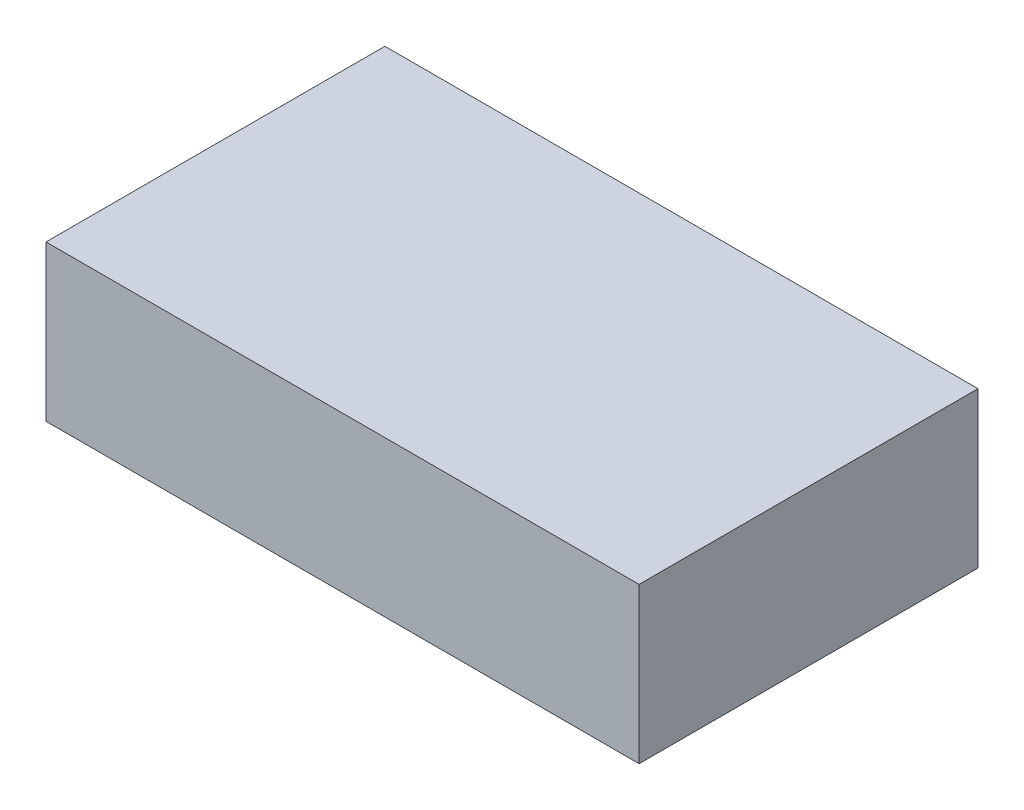
SolidWorks part; units mm, degrees
ref_plane "Front Plane" through (0, 0, 0) normal (0, 0, 1) x (1, 0, 0)
ref_plane "Top Plane" through (0, 0, 0) normal (0, 1, 0) x (1, 0, 0)
ref_plane "Right Plane" through (0, 0, 0) normal (1, 0, 0) x (0, 0, -1)
sketch "Sketch1" plane through (0, 0, 0) normal (0, 1, 0) x (1, 0, 0)
  line L1 (0, 0) -> (42, 0)
  line L2 (0, 0) -> (0, 24)
  line L3 (0, 24) -> (42, 24)
  line L4 (42, 0) -> (42, 24)
  dimension "D1" = 42
  dimension "D2" = 24
extrude "Boss-Extrude1" add sketch "Sketch1" along normal blind 11
